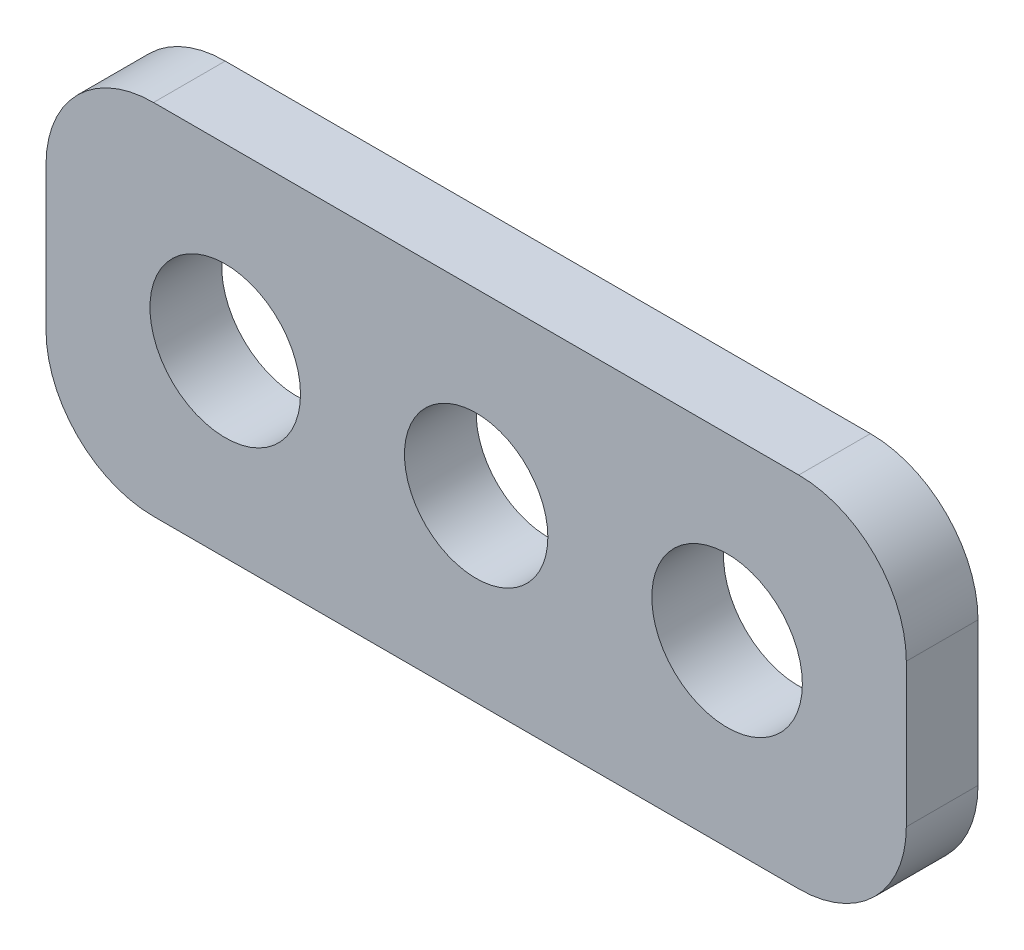
SolidWorks part; units mm, degrees
ref_plane "Front Plane" through (0, 0, 0) normal (0, 0, 1) x (1, 0, 0)
ref_plane "Top Plane" through (0, 0, 0) normal (0, 1, 0) x (1, 0, 0)
ref_plane "Right Plane" through (0, 0, 0) normal (1, 0, 0) x (0, 0, -1)
sketch "Sketch1" plane through (0, 0, 0) normal (0, 0, 1) x (1, 0, 0)
  line L1 (-3.05, 1.4) -> (5.95, 1.4)
  line L2 (-4.55, 2.9) -> (-4.55, 4.9)
  line L3 (-3.05, 6.4) -> (5.95, 6.4)
  line L4 (7.45, 2.9) -> (7.45, 4.9)
  line L5 (-4.55, 1.4) -> (7.45, 6.4) construction
  line L6 (-4.55, 6.4) -> (7.45, 1.4) construction
  circle A2 centre (-2.05, 3.9) radius 1.05
  circle A3 centre (4.95, 3.9) radius 1.05
  arc A4 (-3.05, 1.4) -> (-4.55, 2.9) centre (-3.05, 2.9) cw
  arc A5 (-4.55, 4.9) -> (-3.05, 6.4) centre (-3.05, 4.9) cw
  arc A6 (5.95, 1.4) -> (7.45, 2.9) centre (5.95, 2.9) ccw
  arc A7 (5.95, 6.4) -> (7.45, 4.9) centre (5.95, 4.9) cw
  circle A8 centre (1.45, 3.9) radius 1
  point P0 (1.45, 3.9)
  dimension "D3" = 2.1
  dimension "D4" = 1.5
  dimension "D5" = 2
  dimension "D1" = 5
  dimension "D2" = 12
extrude "Boss-Extrude1" add sketch "Sketch1" along normal blind 1
